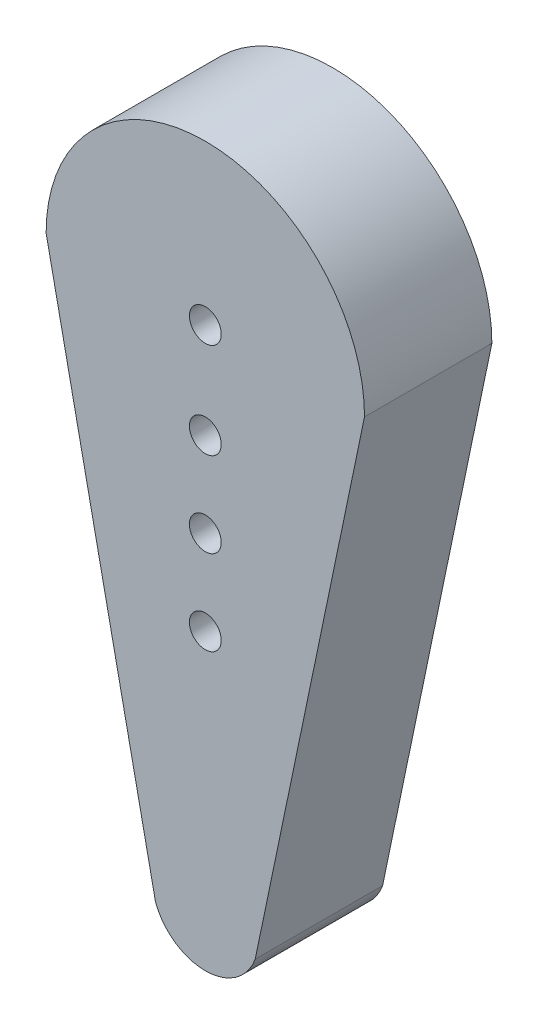
SolidWorks part; units mm, degrees
ref_plane "Front Plane" through (0, 0, 0) normal (0, 0, 1) x (1, 0, 0)
ref_plane "Top Plane" through (0, 0, 0) normal (0, 1, 0) x (1, 0, 0)
ref_plane "Right Plane" through (0, 0, 0) normal (1, 0, 0) x (0, 0, -1)
sketch "Sketch2" plane through (0, 0, 0) normal (0, 0, 1) x (1, 0, 0)
  line L0 (0, -55) -> (0, 55) construction
  line L1 (-7.5, 0) -> (-2.3473, -24.7102)
  line L2 (7.5, 0) -> (2.3504, -24.7019)
  arc A0 (7.5, 0) -> (-7.5, 0) centre (0, 0) ccw
  arc A1 (-2.3473, -24.7102) -> (2.3504, -24.7019) centre (0, -23.85) ccw
  dimension "D1" = 15
  dimension "D2" = 5
  dimension "D3" = 26.35
extrude "Boss-Extrude1" add sketch "Sketch2" along normal blind 6
sketch "Sketch3" plane through (0, 0, 0) normal (0, 0, 1) x (1, 0, 0)
  line L0 (-3.75, 0) -> (-2.25, -15)
  line L1 (2.25, -15) -> (3.75, 0)
  line L2 (0, -1.65) -> (0, 1.65) construction
  arc A0 (3.75, 0) -> (-3.75, 0) centre (0, 0) ccw
  arc A1 (-2.25, -15) -> (2.25, -15) centre (0, -15) ccw
  dimension "D1" = 7.5
  dimension "D2" = 4.5
  dimension "D3" = 15
extrude "Cut-Extrude3" cut sketch "Sketch3" along normal blind 4.7
sketch "Sketch4" plane through (0, 0, 4.7) normal (0, 0, -1) x (-1, 0, 0)
  circle A0 centre (0, 0) radius 0.75
  dimension "D1" = 1.5
extrude "Cut-Extrude4" cut sketch "Sketch4" against normal through all both and the other way through all
sketch "Sketch6" plane through (0, 0, 4.7) normal (0, 0, -1) x (-1, 0, 0)
  line L0 (0, 55) -> (0, -55) construction
  line L1 (55, 0) -> (-55, 0) construction
  circle A0 centre (0, -4.5) radius 0.75
  dimension "D1" = 1.5
  dimension "D2" = 4.5
extrude "Cut-Extrude6" cut sketch "Sketch6" against normal through all both and the other way through all
pattern_linear "LPattern1" count 3 spacing 4 along (0, -1, 0) of "Cut-Extrude6"
